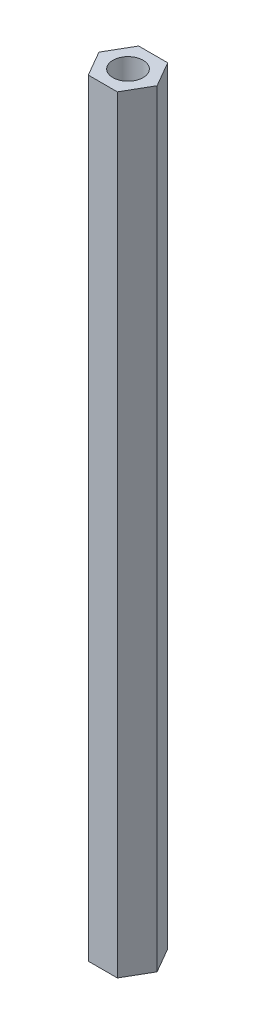
SolidWorks part; units mm, degrees
ref_plane "Front Plane" through (0, 0, 0) normal (0, 0, 1) x (1, 0, 0)
ref_plane "Top Plane" through (0, 0, 0) normal (0, 1, 0) x (1, 0, 0)
ref_plane "Right Plane" through (0, 0, 0) normal (1, 0, 0) x (0, 0, -1)
sketch "Sketch1" plane through (0, 0, 0) normal (0, 1, 0) x (1, 0, 0)
  line L1 (2.8868, 0) -> (1.4434, 2.5)
  line L2 (1.4434, 2.5) -> (-1.4434, 2.5)
  line L3 (-1.4434, 2.5) -> (-2.8868, 0)
  line L4 (-2.8868, 0) -> (-1.4434, -2.5)
  line L5 (-1.4434, -2.5) -> (1.4434, -2.5)
  line L6 (1.4434, -2.5) -> (2.8868, 0)
  circle A0 centre (0, 0) radius 2.5 construction
  dimension "D1" = 5
extrude "Boss-Extrude1" add sketch "Sketch1" along normal blind 76.2
sketch "Sketch2" plane through (0, 76.2, 0) normal (0, 1, 0) x (1, 0, 0)
  circle A0 centre (0, 0) radius 1.5
  dimension "D1" = 3
extrude "Cut-Extrude1" cut sketch "Sketch2" against normal through all
